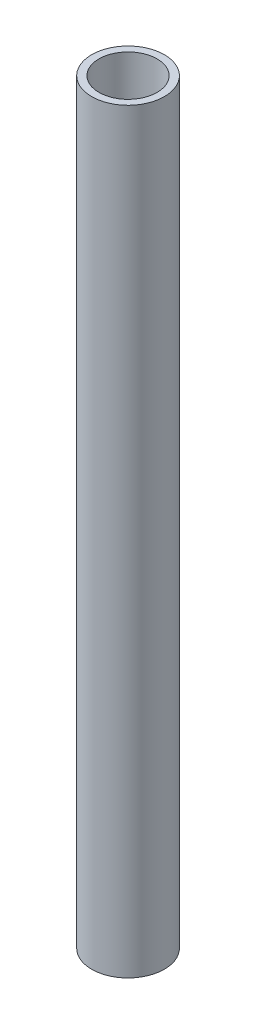
SolidWorks part; units mm, degrees
ref_plane "Front Plane" through (0, 0, 0) normal (0, 0, 1) x (1, 0, 0)
ref_plane "Top Plane" through (0, 0, 0) normal (0, 1, 0) x (1, 0, 0)
ref_plane "Right Plane" through (0, 0, 0) normal (1, 0, 0) x (0, 0, -1)
sketch "Sketch1" plane through (0, 0, 0) normal (0, 1, 0) x (1, 0, 0)
  circle A0 centre (0, 0) radius 1.25
  circle A1 centre (0, 0) radius 1
extrude "Boss-Extrude1" add sketch "Sketch1" along normal blind 26
